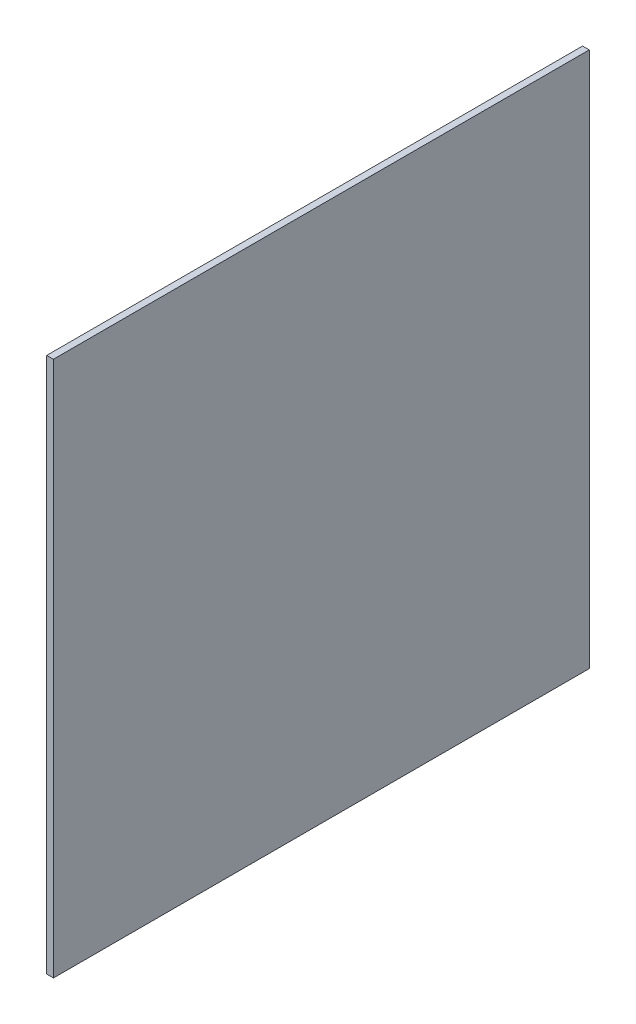
SolidWorks part; units mm, degrees
material "PC High Viscosity"
ref_plane "Front Plane" through (0, 0, 0) normal (0, 0, 1) x (1, 0, 0)
ref_plane "Top Plane" through (0, 0, 0) normal (0, 1, 0) x (1, 0, 0)
ref_plane "Right Plane" through (0, 0, 0) normal (1, 0, 0) x (0, 0, -1)
sketch "Sketch1" plane through (0, 0, 0) normal (1, 0, 0) x (0, 0, -1)
  line L1 (-127, -127) -> (127, -127)
  line L2 (-127, -127) -> (-127, 127)
  line L3 (-127, 127) -> (127, 127)
  line L4 (127, -127) -> (127, 127)
  line L5 (-127, -127) -> (127, 127) construction
  line L6 (-127, 127) -> (127, -127) construction
  point P0 (0, 0)
  dimension "D1" = 254
  dimension "D2" = 254
extrude "Boss-Extrude1" add sketch "Sketch1" along normal blind 3.175
